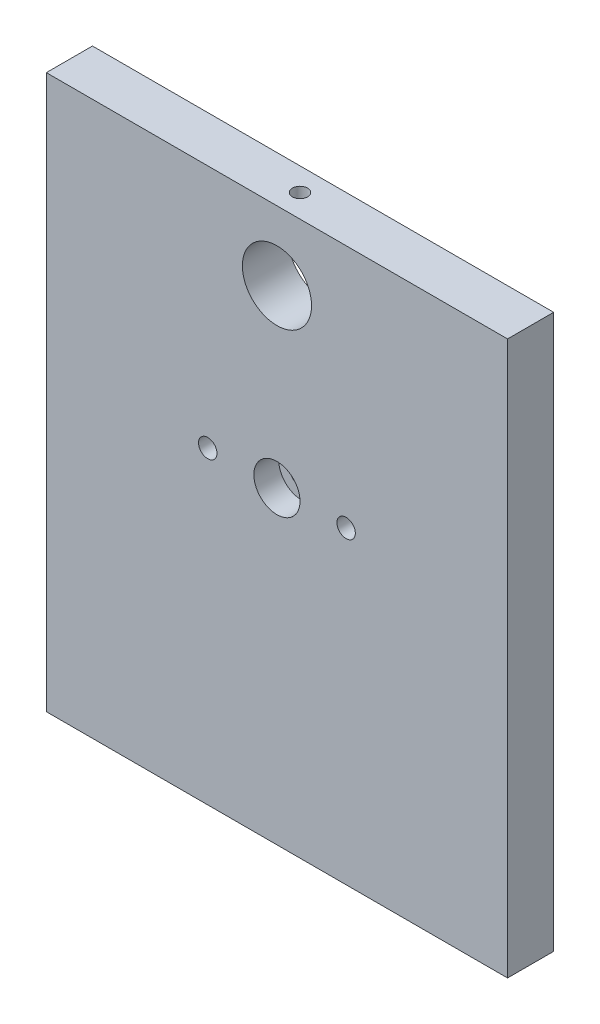
SolidWorks part; units mm, degrees
material "3.3547 (EN-AW 5083)"
ref_plane "Vorne" through (0, 0, 0) normal (0, 0, 1) x (1, 0, 0)
ref_plane "Oben" through (0, 0, 0) normal (0, 1, 0) x (1, 0, 0)
ref_plane "Rechts" through (0, 0, 0) normal (1, 0, 0) x (0, 0, -1)
sketch "Skizze1" plane through (0, 0, 0) normal (0, 0, 1) x (1, 0, 0)
  line L0 (55, 0) -> (-55, 0) construction
  line L1 (-50, 0) -> (50, 0)
  line L2 (-50, 0) -> (-50, 120)
  line L3 (-50, 120) -> (50, 120)
  line L4 (50, 0) -> (50, 120)
  line L5 (0, -55) -> (0, 55) construction
  point P6 (0, 120)
  dimension "D1" = 120
  dimension "D2" = 100
extrude "Aufsatz-Linear austragen1" add sketch "Skizze1" along normal blind 10
hole_wizard "Ø15.0 (15) Durchmesser Bohrung1" positions "Skizze2" profile "Skizze3" hole size "Ø15.0" standard "DIN" end condition through all
sketch "Skizze2" plane through (0, 0, 10) normal (0, 0, 1) x (1, 0, 0)
  line L0 (0, -5.5) -> (0, 5.5) construction
  line L1 (5.5, 0) -> (-5.5, 0) construction
  point P0 (0, 105)
  dimension "D1" = 105
sketch "Skizze3" plane through (0, 105, 10) normal (1, 0, 0) x (0, -1, 0)
  line L0 (0, 0) -> (0, 10)
  line L1 (0, 10) -> (7.5, 10)
  line L2 (7.5, 10) -> (7.5, 0)
  line L5 (7.5, 0) -> (0, 0)
  line L11 (0, -6.35) -> (0, 107.95) construction
  dimension "Bohrerdurchmesser" = 15
  dimension "Bohrungstiefe" = 10
hole_wizard "M5 Gewindebohrung1" positions "Skizze4" profile "Skizze5" tap size "M5" standard "DIN"
sketch "Skizze4" plane through (0, 0, 0) normal (0, -1, 0) x (-1, 0, 0)
  line L0 (0, 5.5) -> (0, -5.5) construction
  line L1 (-55, 0) -> (55, 0) construction
  point P0 (0, -5)
  point P4 (35, -5)
  point P6 (-35, -5)
  dimension "D1" = 35
  dimension "D2" = 35
  dimension "D3" = 5
sketch "Skizze5" plane through (0, 0, 5) normal (1, 0, 0) x (0, 0, -1)
  line L0 (0, 0) -> (0, 15.2618)
  line L1 (0, 15.2618) -> (2.1, 14)
  line L2 (2.1, 14) -> (2.1, 0)
  line L5 (2.1, 0) -> (0, 0)
  line L10 (0, 15.2618) -> (-2.1, 14) construction
  line L11 (0, -6.35) -> (0, 107.95) construction
  dimension "Bohrerdurchmesser" = 4.2
  dimension "Bohrungstiefe" = 14
  dimension "Spitzenwinkel" = 118
cosmetic thread "Bohrungsgewinde1"
cosmetic thread "Bohrungsgewinde2"
cosmetic thread "Bohrungsgewinde3"
hole_wizard "M4 Gewindebohrung1" positions "Skizze6" profile "Skizze7" tap size "M4" standard "DIN"
sketch "Skizze6" plane through (0, 120, 0) normal (0, 1, 0) x (1, 0, 0)
  line L0 (0, -5.5) -> (0, 5.5) construction
  line L1 (-55, 0) -> (55, 0) construction
  point P0 (0, -5)
  dimension "D1" = 5
sketch "Skizze7" plane through (0, 120, 5) normal (1, 0, 0) x (0, 0, 1)
  line L0 (0, 0) -> (0, 12.4914)
  line L1 (0, 12.4914) -> (1.65, 11.5)
  line L2 (1.65, 11.5) -> (1.65, 0)
  line L5 (1.65, 0) -> (0, 0)
  line L10 (0, 12.4914) -> (-1.65, 11.5) construction
  line L11 (0, -6.35) -> (0, 107.95) construction
  dimension "Bohrerdurchmesser" = 3.3
  dimension "Bohrungstiefe" = 11.5
  dimension "Spitzenwinkel" = 118
cosmetic thread "Bohrungsgewinde4"
hole_wizard "Stirnsenkung für M5 Zylinderschraube mit Innensechskant2" positions "Skizze12" profile "Skizze13" counterbore size "M5" standard "DIN" end condition through all
sketch "Skizze12" plane through (0, 0, 10) normal (0, 0, 1) x (1, 0, 0)
  line L0 (0, -5.5) -> (0, 5.5) construction
  line L1 (5.5, 0) -> (-5.5, 0) construction
  point P0 (0, 67)
  dimension "D1" = 67
sketch "Skizze13" plane through (0, 67, 10) normal (1, 0, 0) x (0, -1, 0)
  line L0 (0, 0) -> (0, 10)
  line L1 (0, 10) -> (2.75, 10)
  line L3 (2.75, 10) -> (2.75, 5.4)
  line L4 (2.75, 5.4) -> (5, 5.4)
  line L5 (5, 5.4) -> (5, 0)
  line L7 (5, 0) -> (0, 0)
  line L11 (0, -6.35) -> (0, 107.95) construction
  dimension "Bohrerdurchmesser" = 5.5
  dimension "Bohrungstiefe" = 10
  dimension "Senkdurchmesser2" = 10
  dimension "Senktiefe2" = 5.4
hole_wizard "Ø4.0 (4) Durchmesser Bohrung2" positions "Skizze14" profile "Skizze15" hole size "Ø4.0" standard "DIN" end condition through all
sketch "Skizze14" plane through (0, 0, 10) normal (0, 0, 1) x (1, 0, 0)
  line L0 (0, 67) -> (-15, 67) construction
  line L1 (0, -5.5) -> (0, 5.5) construction
  point P1 (-15, 67)
  point P7 (15, 67)
  dimension "D1" = 15
  dimension "D2" = 30
sketch "Skizze15" plane through (15, 67, 10) normal (1, 0, 0) x (0, -1, 0)
  line L0 (0, 0) -> (0, 10)
  line L1 (0, 10) -> (2, 10)
  line L2 (2, 10) -> (2, 0)
  line L5 (2, 0) -> (0, 0)
  line L11 (0, -6.35) -> (0, 107.95) construction
  dimension "Bohrerdurchmesser" = 4
  dimension "Bohrungstiefe" = 10
